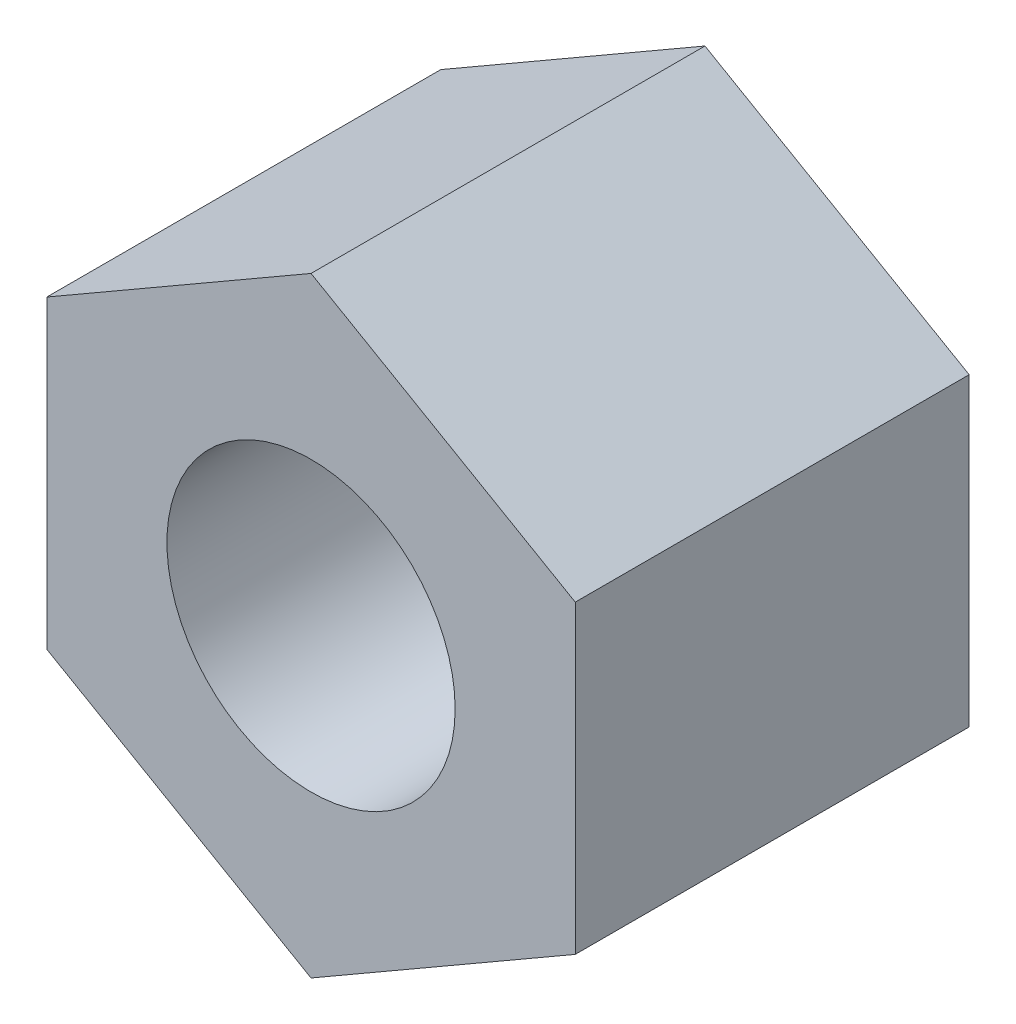
SolidWorks part; units mm, degrees
ref_plane "Front Plane" through (0, 0, 0) normal (0, 0, 1) x (1, 0, 0)
ref_plane "Top Plane" through (0, 0, 0) normal (0, 1, 0) x (1, 0, 0)
ref_plane "Right Plane" through (0, 0, 0) normal (1, 0, 0) x (0, 0, -1)
sketch "Эскиз1" plane through (0, 0, 0) normal (0, 0, 1) x (1, 0, 0)
  line L1 (2.75, 1.5877) -> (0, 3.1754)
  line L2 (0, 3.1754) -> (-2.75, 1.5877)
  line L3 (-2.75, 1.5877) -> (-2.75, -1.5877)
  line L4 (-2.75, -1.5877) -> (0, -3.1754)
  line L5 (0, -3.1754) -> (2.75, -1.5877)
  line L6 (2.75, -1.5877) -> (2.75, 1.5877)
  circle A0 centre (0, 0) radius 2.75 construction
  circle A2 centre (0, 0) radius 1.5
  dimension "D2" = 3
  dimension "D1" = 5.5
extrude "Бобышка-Вытянуть1" add sketch "Эскиз1" along normal blind 4.1
